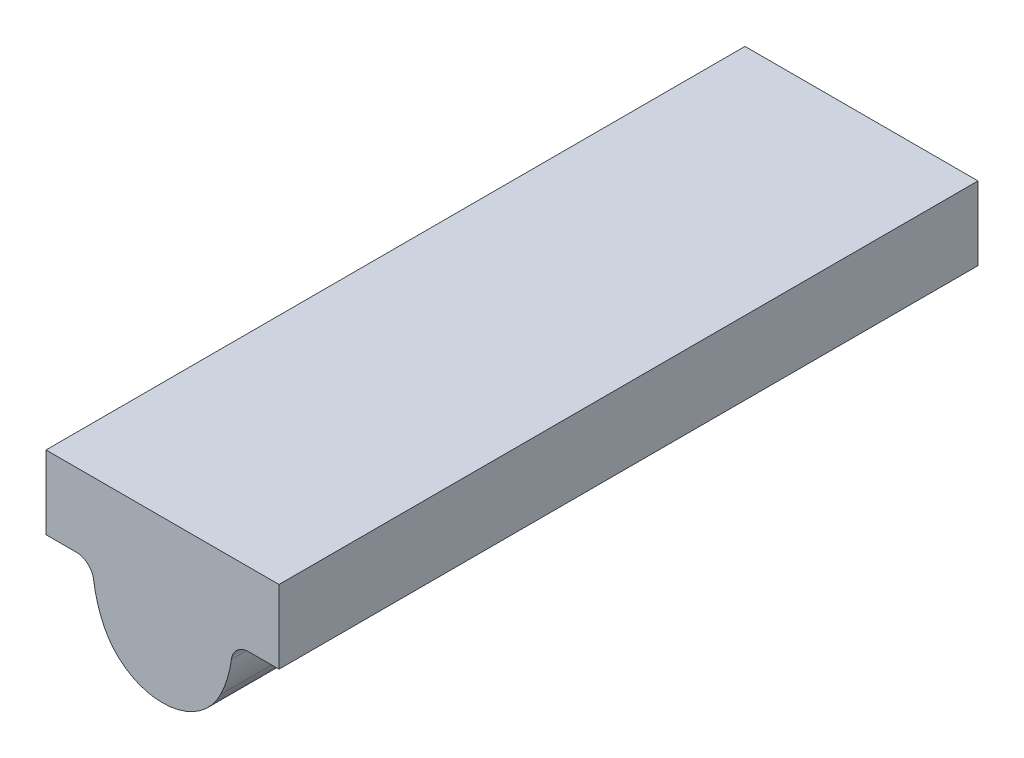
SolidWorks part; units mm, degrees
ref_plane "Piano frontale" through (0, 0, 0) normal (0, 0, 1) x (1, 0, 0)
ref_plane "Piano superiore" through (0, 0, 0) normal (0, 1, 0) x (1, 0, 0)
ref_plane "Piano destro" through (0, 0, 0) normal (1, 0, 0) x (0, 0, -1)
sketch "Schizzo1" plane through (0, 0, 0) normal (0, 0, 1) x (1, 0, 0)
  line L0 (0, 0) -> (0, 1.38) construction
  line L1 (0.7402, 0.75) -> (1, 0.75)
  line L2 (-1, 1.38) -> (1, 1.38)
  line L3 (0.7402, 0.75) -> (-0.7402, 0.75) construction
  line L4 (-0.7402, 0.75) -> (-1, 0.75)
  line L5 (1, 1.38) -> (1, 0.75)
  line L6 (-1, 1.38) -> (-1, 0.75)
  arc A0 (-0.7402, 0.75) -> (-0.5915, 0.6196) centre (-0.7402, 0.6) cw
  arc A1 (0.4989, 0.3118) -> (0.5915, 0.6196) centre (-0.4, 0.75) ccw
  arc A2 (0.7402, 0.75) -> (0.5915, 0.6196) centre (0.7402, 0.6) ccw
  arc A3 (-0.4989, 0.3118) -> (0.4989, 0.3118) centre (0, 0.555) ccw
  arc A4 (-0.4989, 0.3118) -> (-0.5915, 0.6196) centre (0.4, 0.75) cw
  point P3 (-0.4, 0.75)
  point P10 (0, 0.75)
  dimension "D3" = 0.75
  dimension "D4" = 0.555
  dimension "D5" = 1
  dimension "D6" = 0.15
  dimension "D1" = 0.4
  dimension "D2" = 1.38
  dimension "D8" = 1
extrude "Estrusione-Estrusione1" add sketch "Schizzo1" along normal mid plane 6
